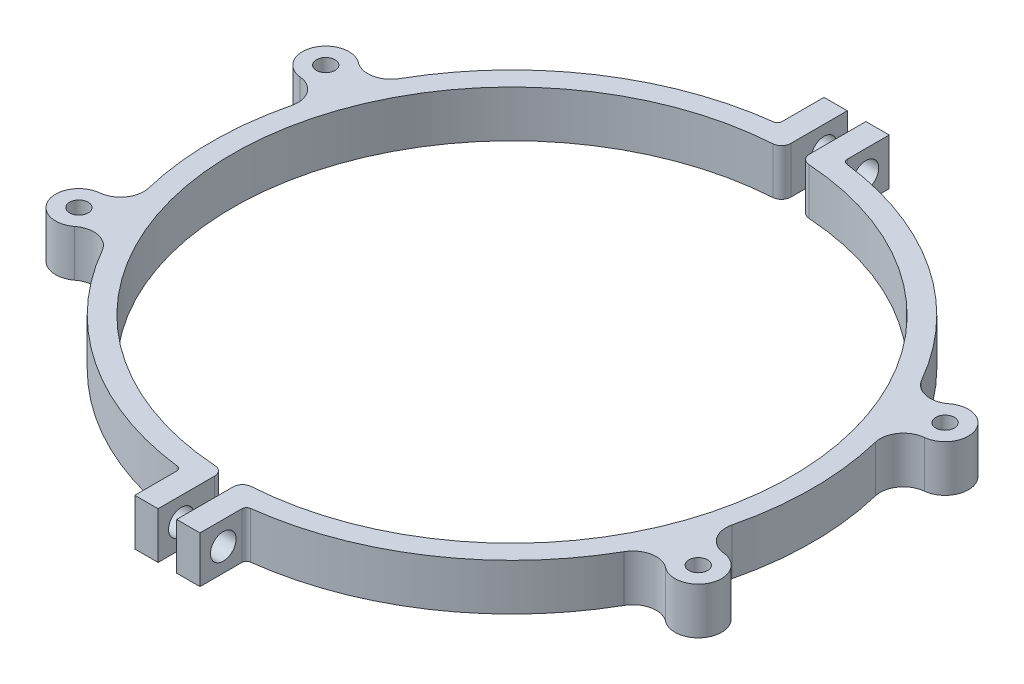
SolidWorks part; units mm, degrees
material "6061 合金"
ref_plane "前视基准面" through (0, 0, 0) normal (0, 0, 1) x (1, 0, 0)
ref_plane "上视基准面" through (0, 0, 0) normal (0, 1, 0) x (1, 0, 0)
ref_plane "右视基准面" through (0, 0, 0) normal (1, 0, 0) x (0, 0, -1)
sketch "草图1" plane through (0, 0, 0) normal (0, 1, 0) x (1, 0, 0)
  line L0 (-7, 65.0096) -> (-7, 74)
  line L1 (-7, 74) -> (-2, 74)
  line L2 (-2, 74) -> (-2, 61.8708)
  line L3 (0, 302.7374) -> (0, 0) construction
  line L4 (0, 0) -> (88.0006, 0) construction
  line L8 (2, 74) -> (2, 61.8708)
  line L9 (7, 74) -> (2, 74)
  line L10 (7, 65.0096) -> (7, 74)
  line L11 (7, -65.0096) -> (7, -74)
  line L12 (7, -74) -> (2, -74)
  line L13 (2, -74) -> (2, -61.8708)
  line L14 (-66.5, 26.5) -> (0, 0) construction
  line L15 (-2, -74) -> (-2, -61.8708)
  line L16 (-7, -74) -> (-2, -74)
  line L17 (-7, -65.0096) -> (-7, -74)
  arc A0 (-3.871, 59.875) -> (-3.871, -59.875) centre (0, 0) ccw
  arc A1 (-62.6445, 15.3595) -> (-62.6445, -15.3595) centre (0, 0) ccw
  arc A2 (-67.0003, 21.5251) -> (-63.4416, 30.4555) centre (-66.5, 26.5) cw
  arc A4 (-7.8779, 64.0171) -> (-56.0391, 31.9354) centre (0, 0) ccw
  arc A5 (-62.6445, 15.3595) -> (-67.0003, 21.5251) centre (-67.5007, 16.5502) ccw
  arc A6 (-56.0391, 31.9354) -> (-63.4416, 30.4555) centre (-60.3832, 34.411) cw
  arc A7 (-3.871, 59.875) -> (-2, 61.8708) centre (-4, 61.8708) ccw
  arc A8 (-7.8779, 64.0171) -> (-7, 65.0096) centre (-8, 65.0096) ccw
  arc A9 (7.8779, 64.0171) -> (7, 65.0096) centre (8, 65.0096) cw
  arc A10 (3.871, 59.875) -> (2, 61.8708) centre (4, 61.8708) cw
  arc A11 (56.0391, 31.9354) -> (63.4416, 30.4555) centre (60.3832, 34.411) ccw
  arc A12 (62.6445, 15.3595) -> (67.0003, 21.5251) centre (67.5007, 16.5502) cw
  arc A14 (67.0003, 21.5251) -> (63.4416, 30.4555) centre (66.5, 26.5) ccw
  arc A15 (56.0391, 31.9354) -> (7.8779, 64.0171) centre (0, 0) ccw
  arc A16 (67.0003, -21.5251) -> (63.4416, -30.4555) centre (66.5, -26.5) cw
  arc A18 (62.6445, -15.3595) -> (67.0003, -21.5251) centre (67.5007, -16.5502) ccw
  arc A19 (56.0391, -31.9354) -> (63.4416, -30.4555) centre (60.3832, -34.411) cw
  arc A20 (-56.0391, -31.9354) -> (-63.4416, -30.4555) centre (-60.3832, -34.411) ccw
  arc A21 (-62.6445, -15.3595) -> (-67.0003, -21.5251) centre (-67.5007, -16.5502) cw
  arc A23 (-67.0003, -21.5251) -> (-63.4416, -30.4555) centre (-66.5, -26.5) ccw
  arc A24 (3.871, -59.875) -> (2, -61.8708) centre (4, -61.8708) ccw
  arc A25 (7.8779, -64.0171) -> (7, -65.0096) centre (8, -65.0096) ccw
  arc A26 (-7.8779, -64.0171) -> (-7, -65.0096) centre (-8, -65.0096) cw
  arc A27 (-3.871, -59.875) -> (-2, -61.8708) centre (-4, -61.8708) cw
  arc A28 (-56.0391, -31.9354) -> (-7.8779, -64.0171) centre (0, 0) ccw
  arc A29 (7.8779, -64.0171) -> (56.0391, -31.9354) centre (0, 0) ccw
  arc A30 (3.871, -59.875) -> (3.871, 59.875) centre (0, 0) ccw
  arc A31 (62.6445, -15.3595) -> (62.6445, 15.3595) centre (0, 0) ccw
  dimension "D1" = 120
  dimension "D2" = 4.5
  dimension "D6" = 5
  dimension "D5" = 5
  dimension "D10" = 1
  dimension "D12" = 2
  dimension "D3" = 4
  dimension "D4" = 5
  dimension "D8" = 53
  dimension "D9" = 133
  dimension "D11" = 148
extrude "凸台-拉伸1" add sketch "草图1" along normal mid plane 10
sketch "草图2" plane through (0, 0, 0) normal (1, 0, 0) x (0, 0, -1)
  line L0 (0, 0) -> (0, 5) construction
  line L1 (15.3595, 5) -> (-15.3595, 5) construction
  line L2 (-74, 5) -> (-74, -5) construction
  circle A0 centre (-69, 0) radius 2.75
  circle A1 centre (69, 0) radius 2.75
  dimension "D1" = 5.5
  dimension "D2" = 5
extrude "切除-拉伸1" cut sketch "草图2" against normal through all both and the other way through all
hole_wizard "Ø4.0 (4) 直径孔1" positions "草图3" profile "草图4" hole size "Ø4.0" standard "GB" end condition through all
sketch "草图3" plane through (0, 5, 0) normal (0, 1, 0) x (1, 0, 0)
  point P0 (-66.5, 26.5)
  point P3 (-66.5, -26.5)
  point P6 (66.5, -26.5)
  point P9 (66.5, 26.5)
sketch "草图4" plane through (-66.5, 5, -26.5) normal (1, 0, 0) x (0, 0, 1)
  line L0 (0, 0) -> (0, 10)
  line L1 (0, 10) -> (2, 10)
  line L2 (2, 10) -> (2, 0)
  line L5 (2, 0) -> (0, 0)
  line L11 (0, -6.35) -> (0, 107.95) construction
  dimension "通孔孔直径" = 4
  dimension "通孔孔深度" = 10
